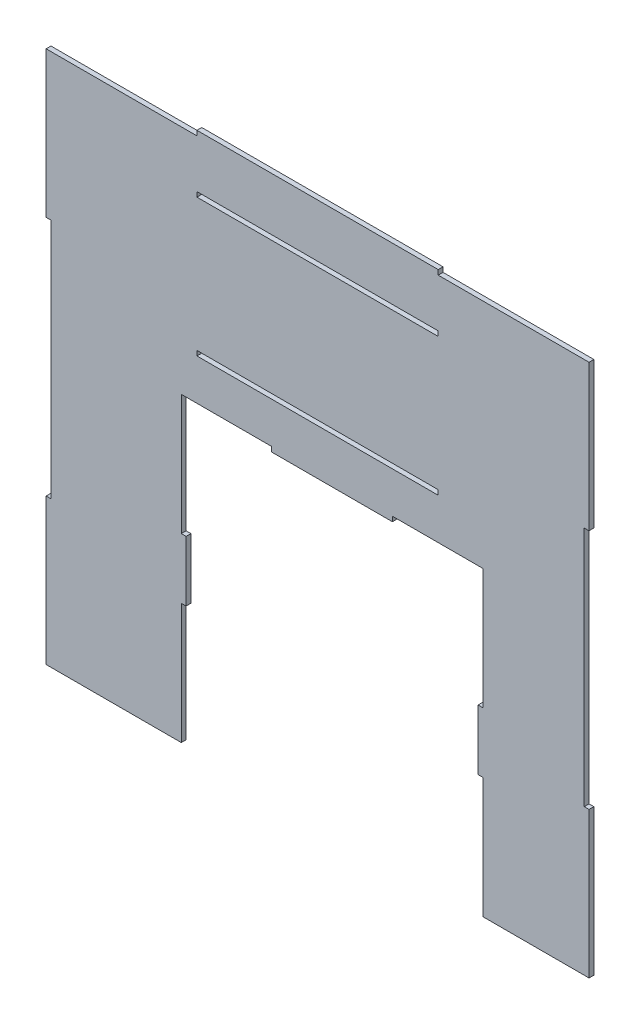
SolidWorks part; units mm, degrees
ref_plane "Front Plane" through (0, 0, 0) normal (0, 0, 1) x (1, 0, 0)
ref_plane "Top Plane" through (0, 0, 0) normal (0, 1, 0) x (1, 0, 0)
ref_plane "Right Plane" through (0, 0, 0) normal (1, 0, 0) x (0, 0, -1)
sketch "Sketch1" plane through (0, 0, 0) normal (0, 0, 1) x (1, 0, 0)
  line L0 (-268.2019, -98.094) -> (-268.2019, -219.094)
  line L1 (-268.2019, -219.094) -> (-156.2019, -219.094)
  line L5 (93.7981, -219.094) -> (181.7981, -219.094)
  line L6 (181.7981, -219.094) -> (181.7981, -98.094)
  line L7 (181.7981, -98.094) -> (177.7981, -98.094)
  line L8 (177.7981, -98.094) -> (177.7981, 101.906)
  line L9 (177.7981, 101.906) -> (181.7981, 101.906)
  line L10 (181.7981, 101.906) -> (181.7981, 222.906)
  line L11 (181.7981, 222.906) -> (56.7981, 222.906)
  line L12 (56.7981, 222.906) -> (56.7981, 226.906)
  line L13 (56.7981, 226.906) -> (-143.2019, 226.906)
  line L14 (-143.2019, 226.906) -> (-143.2019, 222.906)
  line L15 (-143.2019, 222.906) -> (-268.2019, 222.906)
  line L16 (-268.2019, 222.906) -> (-268.2019, 101.906)
  line L17 (-268.2019, 101.906) -> (-264.2019, 101.906)
  line L18 (-264.2019, 101.906) -> (-264.2019, -98.094)
  line L19 (-264.2019, -98.094) -> (-268.2019, -98.094)
  line L20 (-156.2019, -119.094) -> (-156.2019, -219.094)
  line L21 (-143.2019, 68.906) -> (56.7981, 68.906)
  line L22 (-143.2019, 68.906) -> (-143.2019, 64.906)
  line L23 (-143.2019, 64.906) -> (56.7981, 64.906)
  line L24 (56.7981, 68.906) -> (56.7981, 64.906)
  line L25 (-143.2019, 182.906) -> (56.7981, 182.906)
  line L26 (-143.2019, 182.906) -> (-143.2019, 178.906)
  line L27 (-143.2019, 178.906) -> (56.7981, 178.906)
  line L28 (56.7981, 182.906) -> (56.7981, 178.906)
  line L29 (93.7981, -219.094) -> (93.7981, -119.094)
  line L30 (93.7981, 30.906) -> (18.7981, 30.906)
  line L31 (-156.2019, 30.906) -> (-156.2019, -69.094)
  line L32 (-156.2019, -69.094) -> (-152.2019, -69.094)
  line L34 (-156.2019, -119.094) -> (-152.2019, -119.094)
  line L35 (-152.2019, -69.094) -> (-152.2019, -119.094)
  line L36 (93.7981, -69.094) -> (89.7981, -69.094)
  line L38 (93.7981, -119.094) -> (89.7981, -119.094)
  line L39 (89.7981, -69.094) -> (89.7981, -119.094)
  line L40 (93.7981, -69.094) -> (93.7981, 30.906)
  line L41 (-81.2019, 30.906) -> (-156.2019, 30.906)
  line L43 (-81.2019, 30.906) -> (-81.2019, 26.906)
  line L44 (-81.2019, 26.906) -> (18.7981, 26.906)
  line L45 (18.7981, 30.906) -> (18.7981, 26.906)
  dimension "D1" = 108
  dimension "D2" = 250
  dimension "D3" = 250
  dimension "D4" = 125
  dimension "D5" = 125
  dimension "D6" = 100
  dimension "D7" = 100
  dimension "D8" = 4
  dimension "D9" = 50
  dimension "D10" = 4
  dimension "D11" = 100
  dimension "D12" = 100
  dimension "D13" = 4
  dimension "D14" = 183
extrude "Boss-Extrude1" add sketch "Sketch1" along normal blind 4
sketch "Sketch2" plane through (0, 0, 4) normal (0, 0, 1) x (1, 0, 0)
  line L20 (-264.2019, -98.094) -> (-268.2019, -98.094)
  line L21 (-268.2019, -98.094) -> (-268.2019, -219.094)
  line L22 (-268.2019, -219.094) -> (-156.2019, -219.094)
  line L23 (-156.2019, -69.094) -> (-156.2019, 30.906)
  line L24 (-156.2019, -69.094) -> (-156.2019, 30.906)
  line L25 (18.7981, 30.906) -> (93.7981, 30.906)
  line L26 (93.7981, -219.094) -> (181.7981, -219.094)
  line L27 (181.7981, -219.094) -> (181.7981, -98.094)
  line L28 (181.7981, -98.094) -> (177.7981, -98.094)
  line L29 (177.7981, -98.094) -> (177.7981, 101.906)
  line L30 (177.7981, 101.906) -> (181.7981, 101.906)
  line L31 (181.7981, 101.906) -> (181.7981, 222.906)
  line L32 (181.7981, 222.906) -> (56.7981, 222.906)
  line L33 (56.7981, 222.906) -> (56.7981, 226.906)
  line L34 (56.7981, 226.906) -> (-143.2019, 226.906)
  line L35 (-143.2019, 226.906) -> (-143.2019, 222.906)
  line L36 (-143.2019, 222.906) -> (-268.2019, 222.906)
  line L37 (-268.2019, 222.906) -> (-268.2019, 101.906)
  line L38 (-268.2019, 101.906) -> (-264.2019, 101.906)
  line L39 (-264.2019, 101.906) -> (-264.2019, -98.094)
  line L40 (-264.2019, -98.094) -> (-268.2019, -98.094)
  line L41 (-268.2019, -98.094) -> (-268.2019, -219.094)
  line L42 (-268.2019, -219.094) -> (-156.2019, -219.094)
  line L46 (93.7981, -219.094) -> (181.7981, -219.094)
  line L47 (181.7981, -219.094) -> (181.7981, -98.094)
  line L48 (181.7981, -98.094) -> (177.7981, -98.094)
  line L49 (177.7981, -98.094) -> (177.7981, 101.906)
  line L50 (177.7981, 101.906) -> (181.7981, 101.906)
  line L51 (181.7981, 101.906) -> (181.7981, 222.906)
  line L52 (181.7981, 222.906) -> (56.7981, 222.906)
  line L53 (56.7981, 222.906) -> (56.7981, 226.906)
  line L54 (56.7981, 226.906) -> (-143.2019, 226.906)
  line L55 (-143.2019, 226.906) -> (-143.2019, 222.906)
  line L56 (-143.2019, 222.906) -> (-268.2019, 222.906)
  line L57 (-268.2019, 222.906) -> (-268.2019, 101.906)
  line L58 (-268.2019, 101.906) -> (-264.2019, 101.906)
  line L59 (-264.2019, 101.906) -> (-264.2019, -98.094)
  line L60 (18.7981, 30.906) -> (93.7981, 30.906)
  line L61 (93.7981, -119.094) -> (93.7981, -219.094)
  line L62 (93.7981, -119.094) -> (93.7981, -219.094)
  line L75 (-156.2019, -219.094) -> (-156.2019, -119.094)
  line L76 (-156.2019, -219.094) -> (-156.2019, -119.094)
  line L77 (-156.2019, -119.094) -> (-152.2019, -119.094)
  line L78 (-156.2019, -119.094) -> (-152.2019, -119.094)
  line L79 (-152.2019, -119.094) -> (-152.2019, -69.094)
  line L80 (-152.2019, -119.094) -> (-152.2019, -69.094)
  line L81 (-152.2019, -69.094) -> (-156.2019, -69.094)
  line L82 (-152.2019, -69.094) -> (-156.2019, -69.094)
  line L83 (-156.2019, 30.906) -> (-81.2019, 30.906)
  line L84 (-156.2019, 30.906) -> (-81.2019, 30.906)
  line L85 (-81.2019, 30.906) -> (-81.2019, 26.906)
  line L86 (-81.2019, 30.906) -> (-81.2019, 26.906)
  line L87 (-81.2019, 26.906) -> (18.7981, 26.906)
  line L88 (-81.2019, 26.906) -> (18.7981, 26.906)
  line L89 (18.7981, 26.906) -> (18.7981, 30.906)
  line L90 (18.7981, 26.906) -> (18.7981, 30.906)
  line L91 (93.7981, 30.906) -> (93.7981, -69.094)
  line L92 (93.7981, 30.906) -> (93.7981, -69.094)
  line L93 (93.7981, -69.094) -> (89.7981, -69.094)
  line L94 (93.7981, -69.094) -> (89.7981, -69.094)
  line L95 (89.7981, -69.094) -> (89.7981, -119.094)
  line L96 (89.7981, -69.094) -> (89.7981, -119.094)
  line L97 (89.7981, -119.094) -> (93.7981, -119.094)
  line L98 (89.7981, -119.094) -> (93.7981, -119.094)
  dimension "D1" = 0
